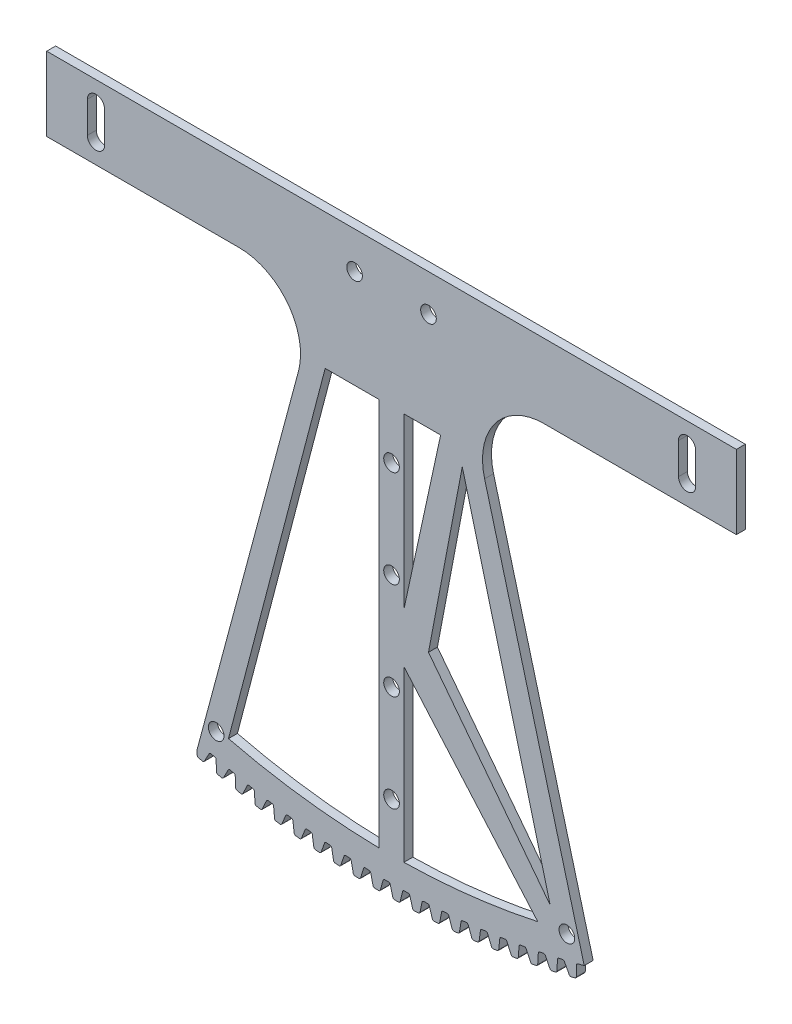
SolidWorks part; units mm, degrees
material "201 Annealed Stainless Steel (SS)"
ref_plane "Front Plane" through (0, 0, 0) normal (0, 0, 1) x (1, 0, 0)
ref_plane "Top Plane" through (0, 0, 0) normal (0, 1, 0) x (1, 0, 0)
ref_plane "Right Plane" through (0, 0, 0) normal (1, 0, 0) x (0, 0, -1)
sketch "Sketch3" plane through (0, 0, 0) normal (0, 0, 1) x (1, 0, 0)
  line L0 (0, 0) -> (0, -304.8) construction
  line L1 (-21.234, -79.2464) -> (-78.888, -294.4142)
  line L2 (21.234, -79.2464) -> (78.888, -294.4142)
  line L4 (-140, -79.56) -> (140, -79.56)
  line L5 (-140, -79.56) -> (-140, -109.56)
  line L6 (-140, -109.56) -> (140, -109.56)
  line L7 (140, -79.56) -> (140, -109.56)
  line L8 (0, -109.56) -> (0, -79.56) construction
  line L9 (-140, -94.56) -> (140, -94.56) construction
  arc A0 (-78.888, -294.4142) -> (78.888, -294.4142) centre (0, 0) ccw
  point P269 (0, -94.56)
  dimension "D1" = 304.8
  dimension "D4" = 79.56
  dimension "D5" = 30
  dimension "D6" = 280
  dimension "D7" = 140
extrude "Boss-Extrude2" add sketch "Sketch3" along normal blind 3.6286 contours L7 L4 L2 L6 | L1 L6 L2 L4 | L1 L4 L2 | L5 L6 L1 L4 | L1 A0 L2 L6
fillet "Fillet1" radius 25 2 edges at (-29.3565, -109.56, 1.8143) (29.3565, -109.56, 1.8143)
sketch "Sketch4" plane through (0, -79.56, 0) normal (0, 1, 0) x (1, 0, 0)
  line L1 (-140, 0) -> (140, 0)
  line L2 (-140, 0) -> (-140, -3.6286)
  line L3 (-140, -3.6286) -> (140, -3.6286)
  line L4 (140, 0) -> (140, -3.6286)
  line L5 (0, -3.6286) -> (0, 0) construction
  line L6 (-140, -1.8143) -> (140, -1.8143) construction
  point P252 (0, -1.8143)
sketch "Sketch5" plane through (0, 0, 0) normal (0, 0, -1) x (-1, 0, 0)
  line L0 (-123.5, -94.56) -> (-123.5, -100.91)
  line L1 (-116.5, -94.56) -> (-116.5, -100.91)
  line L2 (116.5, -94.56) -> (116.5, -88.21)
  line L3 (140, -79.56) -> (-140, -79.56) construction
  line L4 (-120, -88.21) -> (-120, -100.91) construction
  line L5 (0, -79.56) -> (0, -109.56) construction
  line L6 (-116.5, -94.56) -> (-116.5, -88.21)
  line L7 (-123.5, -94.56) -> (-123.5, -88.21)
  line L8 (116.5, -94.56) -> (116.5, -100.91)
  line L9 (123.5, -94.56) -> (123.5, -100.91)
  line L10 (123.5, -94.56) -> (123.5, -88.21)
  line L11 (-140, -79.56) -> (-140, -109.56) construction
  line L12 (120, -88.21) -> (120, -100.91) construction
  arc A1 (-116.5, -88.21) -> (-123.5, -88.21) centre (-120, -88.21) ccw
  arc A2 (-123.5, -100.91) -> (-116.5, -100.91) centre (-120, -100.91) ccw
  arc A3 (123.5, -100.91) -> (116.5, -100.91) centre (120, -100.91) cw
  arc A4 (116.5, -88.21) -> (123.5, -88.21) centre (120, -88.21) cw
  circle A5 centre (-15, -94.56) radius 3.175
  circle A6 centre (15, -94.56) radius 3.175
  dimension "D1" = 16.5
  dimension "D2" = 7
  dimension "D3" = 8.65
  dimension "D5" = 3.5
  dimension "D6" = 15
  dimension "D8" = 6.35
  dimension "D4" = 6.35
  dimension "D7" = 15
sketch "Sketch13" plane through (0, 0, 0) normal (0, 0, -1) x (-1, 0, 0)
  line L0 (0, 0) -> (78.888, -294.4142)
  line L1 (0, 0) -> (-78.888, -294.4142)
  arc A0 (-78.888, -294.4142) -> (78.888, -294.4142) centre (0, 0) ccw
  arc A1 (-78.888, -294.4142) -> (78.888, -294.4142) centre (0, 0) ccw construction
  arc A2 (-78.888, -294.4142) -> (78.888, -294.4142) centre (0, 0) ccw
  circle A3 centre (0, 0) radius 304.8
  dimension "D1" = 609.6
sketch "Sketch14" plane through (0, 0, 0) normal (0, 0, -1) x (-1, 0, 0)
  line L0 (0, 0) -> (80.0203, -298.6399) construction
  line L2 (78.888, -294.4142) -> (78.9109, -297.0369)
  line L3 (78.9109, -297.0369) -> (76.2891, -297.7211)
  line L18 (76.2891, -297.7211) -> (75.0275, -295.4216)
  line L20 (0, 0) -> (-79.2746, -295.8555) construction
  line L32 (78.888, -294.4142) -> (75.0275, -295.4216)
  line L33 (75.0275, -295.4216) -> (78.888, -294.4142)
  line L34 (0, 0) -> (-75.3952, -296.8678) construction
  line L35 (0, 0) -> (-71.5028, -297.8293) construction
  line L36 (0, 0) -> (-67.5982, -298.7397) construction
  line L37 (0, 0) -> (-63.6821, -299.5989) construction
  line L38 (0, 0) -> (-59.755, -300.4068) construction
  line L39 (0, 0) -> (-55.8176, -301.1633) construction
  line L40 (0, 0) -> (-51.8707, -301.8681) construction
  line L41 (0, 0) -> (-47.9149, -302.5212) construction
  line L42 (0, 0) -> (-43.951, -303.1225) construction
  line L43 (0, 0) -> (-39.9794, -303.6718) construction
  line L44 (0, 0) -> (-36.0011, -304.1691) construction
  line L45 (0, 0) -> (-32.0165, -304.6143) construction
  line L46 (0, 0) -> (-28.0265, -305.0073) construction
  line L47 (0, 0) -> (-24.0316, -305.348) construction
  line L48 (0, 0) -> (-20.0327, -305.6364) construction
  line L49 (0, 0) -> (-16.0303, -305.8724) construction
  line L50 (0, 0) -> (-12.0252, -306.0561) construction
  line L51 (0, 0) -> (-8.018, -306.1873) construction
  line L52 (0, 0) -> (-4.0094, -306.266) construction
  line L53 (0, 0) -> (-0.0002, -306.2922) construction
  line L54 (0, 0) -> (4.0091, -306.266) construction
  line L55 (0, 0) -> (8.0176, -306.1873) construction
  line L56 (0, 0) -> (12.0248, -306.0561) construction
  line L57 (0, 0) -> (16.03, -305.8725) construction
  line L58 (0, 0) -> (20.0323, -305.6364) construction
  line L59 (0, 0) -> (24.0313, -305.348) construction
  line L60 (0, 0) -> (28.0261, -305.0073) construction
  line L61 (0, 0) -> (32.0162, -304.6143) construction
  line L62 (0, 0) -> (36.0007, -304.1691) construction
  line L63 (0, 0) -> (39.9791, -303.6719) construction
  line L64 (0, 0) -> (43.9506, -303.1225) construction
  line L65 (0, 0) -> (47.9146, -302.5213) construction
  line L66 (0, 0) -> (51.8704, -301.8682) construction
  line L67 (0, 0) -> (55.8173, -301.1633) construction
  line L68 (0, 0) -> (59.7546, -300.4069) construction
  line L69 (0, 0) -> (63.6817, -299.599) construction
  line L70 (0, 0) -> (67.5979, -298.7398) construction
  line L71 (0, 0) -> (71.5025, -297.8293) construction
  line L72 (0, 0) -> (75.3948, -296.8679) construction
  line L73 (0, 0) -> (-79.2746, -295.8555) construction
  line L74 (0, 0) -> (-75.3952, -296.8678) construction
  line L137 (37.789, -141.0305) -> (78.888, -294.4142) construction
  line L138 (-140, -79.56) -> (-140, -109.56)
  line L139 (-140, -109.56) -> (-61.9371, -109.56)
  line L140 (-37.789, -141.0305) -> (-78.888, -294.4142)
  line L141 (78.888, -294.4142) -> (37.789, -141.0305)
  line L142 (61.9371, -109.56) -> (140, -109.56)
  line L143 (140, -109.56) -> (140, -79.56)
  line L144 (140, -79.56) -> (-140, -79.56)
  line L145 (-140, -79.56) -> (-140, -109.56)
  line L146 (-140, -109.56) -> (-61.9371, -109.56)
  line L147 (-37.789, -141.0305) -> (-78.888, -294.4142)
  line L149 (61.9371, -109.56) -> (140, -109.56)
  line L150 (140, -109.56) -> (140, -79.56)
  line L151 (140, -79.56) -> (-140, -79.56)
  circle A0 centre (0, 0) radius 307.34
  circle A1 centre (0, 0) radius 302.26
  arc A3 (-37.789, -141.0305) -> (-61.9371, -109.56) centre (-61.9371, -134.56) ccw
  arc A5 (61.9371, -109.56) -> (37.789, -141.0305) centre (61.9371, -134.56) ccw
  arc A6 (-37.789, -141.0305) -> (-61.9371, -109.56) centre (-61.9371, -134.56) ccw
  arc A8 (61.9371, -109.56) -> (37.789, -141.0305) centre (61.9371, -134.56) ccw
  arc A11 (-78.888, -294.4142) -> (78.888, -294.4142) centre (0, 0) ccw
  arc A12 (-78.888, -294.4142) -> (78.888, -294.4142) centre (0, 0) ccw
  dimension "D5" = 614.68
  dimension "D6" = 30
  dimension "D7" = 40
  dimension "D4" = 604.52
  dimension "D1" = 14.5
  dimension "D3" = 14.5
  dimension "D8" = 0.75
  dimension "D9" = 306.2922
  dimension "D10" = 0.75
  dimension "D2" = 0
extrude "Boss-Extrude4" add sketch "Sketch14" against normal up to surface (3.6286 mm away) up to face at (0, -146.6727, 3.6286)
sketch "Sketch15" plane through (0, 0, 0) normal (1, 0, 0) x (0, 0, -1)
  line L0 (0, 0) -> (-23.3364, 0) construction
sketch "Sketch16" plane through (0, 0, 0) normal (0, 0, -1) x (-1, 0, 0)
  line L0 (75.0275, -295.4216) -> (73.7653, -293.1208)
  line L1 (73.7653, -293.1208) -> (71.1999, -293.7544)
  line L2 (71.1999, -293.7544) -> (71.1541, -296.3784)
  line L3 (0, 0) -> (71.5025, -297.8293) construction
  line L4 (0, 0) -> (75.3948, -296.8679) construction
  circle A0 centre (0, 0) radius 302.26 construction
  arc A1 (-78.888, -294.4142) -> (78.888, -294.4142) centre (0, 0) ccw construction
  dimension "D1" = 14.5
  dimension "D2" = 14.5
extrude "Cut-Extrude2" cut sketch "Sketch16" against normal through all and the other way through all
fillet "Fillet2" radius 0.73 2 edges at (-76.2891, -297.7211, 1.8143) (-78.9109, -297.0369, 1.8143)
pattern_circular "CirPattern8" count 20 every 1.5 about axis through (0, 0, 0) along (0, 0, 1) of "Cut-Extrude2", "Boss-Extrude4", "Fillet2"
extrude "Cut-Extrude3" cut sketch "Sketch5" against normal through all
sketch "Sketch17" plane through (0, 0, 0) normal (0, 0, -1) x (-1, 0, 0)
  line L0 (0, -79.56) -> (0, -134.56) construction
  line L1 (140, -79.56) -> (-140, -79.56) construction
  line L2 (-61.9371, -109.56) -> (61.9371, -109.56) construction
  line L3 (-36.9371, -134.56) -> (-26.9371, -134.56) construction
  line L4 (-36.9371, -134.56) -> (-26.9371, -134.56) construction
  line L5 (-26.9371, -134.56) -> (-66.1944, -284.3612) construction
  line L6 (-66.1944, -284.3612) -> (-76.1944, -284.3612) construction
  line L7 (0, -292.2593) -> (5, -292.2593) construction
  line L8 (-37.789, -141.0305) -> (-78.888, -294.4142) construction
  line L9 (0, -134.56) -> (-5, -134.56) construction
  line L10 (0, -134.56) -> (5, -134.56) construction
  line L11 (26.9371, -134.56) -> (36.9371, -134.56) construction
  line L12 (-5, -134.56) -> (-5, -292.2593) construction
  line L13 (36.9371, -134.56) -> (26.9371, -134.56) construction
  line L14 (26.9371, -134.56) -> (66.1944, -284.3612) construction
  line L15 (66.1944, -284.3612) -> (76.1944, -284.3612) construction
  line L16 (37.789, -141.0305) -> (78.888, -294.4142) construction
  line L17 (0.6571, -302.2593) -> (-3.5916, -302.2593) construction
  line L18 (-5, -134.56) -> (5, -134.56) construction
  line L19 (-3.5916, -292.2593) -> (-5, -292.2593) construction
  line L20 (5, -134.56) -> (5, -292.2593) construction
  line L21 (-3.5916, -302.2593) -> (-3.5916, -292.2593) construction
  line L22 (0, -193.6972) -> (0, -233.1221) construction
  line L24 (-66.1944, -284.3612) -> (-68.6354, -294.3612) construction
  line L25 (-67.3487, -294.6613) -> (-69.9221, -294.0612) construction
  line L26 (71.1999, -293.7544) -> (66.067, -294.9513) construction
  line L27 (66.1944, -284.3612) -> (68.6335, -294.3529) construction
  line L28 (26.9371, -134.56) -> (66.1944, -284.3612)
  line L29 (26.9371, -134.56) -> (5, -134.56)
  line L30 (5, -134.56) -> (5, -292.2593)
  line L31 (-66.1944, -284.3612) -> (-26.9371, -134.56)
  line L32 (-26.9371, -134.56) -> (-5, -134.56)
  line L33 (-5, -134.56) -> (-5, -292.2593)
  line L35 (66.1944, -284.3612) -> (57.6779, -286.2946)
  line L36 (66.1944, -284.3612) -> (64.4199, -277.5899) construction
  line L41 (26.9371, -134.56) -> (28.7117, -141.3313) construction
  line L42 (26.9371, -134.56) -> (19.9371, -134.56) construction
  line L44 (28.7117, -141.3313) -> (26.9371, -134.56) construction
  line L48 (-59.3729, -285.9321) -> (-5, -223.4096)
  line L50 (-64.4199, -277.5899) -> (-15, -213.4096)
  line L51 (-15, -213.4096) -> (-28.7117, -141.3313)
  line L52 (-5, -203.4096) -> (-19.9371, -134.56)
  circle A0 centre (0, -272.5469) radius 3.175
  arc A1 (61.9371, -109.56) -> (37.789, -141.0305) centre (61.9371, -134.56) ccw construction
  arc A2 (-37.789, -141.0305) -> (-61.9371, -109.56) centre (-61.9371, -134.56) ccw construction
  arc A3 (-66.1944, -284.3612) -> (-5, -292.2593) centre (0, -12.5018) ccw
  arc A4 (5, -292.2593) -> (66.1944, -284.3612) centre (0, -12.5018) ccw
  circle A5 centre (0, -233.1221) radius 3.175
  circle A6 centre (0, -193.6972) radius 3.175
  circle A7 centre (0, -154.2724) radius 3.175
  circle A8 centre (-71.1944, -284.3612) radius 3.175
  circle A9 centre (71.1944, -284.3612) radius 3.175
  arc A13 (19.9371, -134.56) -> (28.7117, -141.3313) centre (26.9371, -134.56) ccw construction
  arc A14 (19.9371, -134.56) -> (28.7117, -141.3313) centre (26.9371, -134.56) ccw construction
  arc A15 (-59.3729, -285.9321) -> (-64.4199, -277.5899) centre (-66.1944, -284.3612) ccw construction
  arc A16 (-64.4199, -277.5899) -> (-59.3729, -285.9321) centre (-66.1944, -284.3612) cw
  arc A17 (-5, -203.4096) -> (-5, -223.4096) centre (-5, -213.4096) ccw construction
  arc A18 (-28.7117, -141.3313) -> (-19.9371, -134.56) centre (-26.9371, -134.56) ccw construction
  arc A19 (5, -223.4096) -> (5, -203.4096) centre (5, -213.4096) ccw construction
  arc A20 (64.4199, -277.5899) -> (59.3729, -285.9321) centre (66.1944, -284.3612) ccw construction
  dimension "D13" = 6.35
  dimension "D14" = 6.35
  dimension "D15" = 10
  dimension "D16" = 7
  dimension "D17" = 7
  dimension "D20" = 7
  dimension "D21" = 10
  dimension "D22" = 7
  dimension "D18" = 7
  dimension "D1" = 10
  dimension "D2" = 5
  dimension "D3" = 10
  dimension "D4" = 10
  dimension "D5" = 5
  dimension "D6" = 5
  dimension "D7" = 10
  dimension "D8" = 10
  dimension "D9" = 5
  dimension "D10" = 10
  dimension "D11" = 157.6993
  dimension "D12" = 10
  dimension "D19" = 12.241
extrude "Cut-Extrude4" cut sketch "Sketch17" against normal through all
fillet "Fillet3" radius 0.7 39 edges at (75.039, -292.7973, 1.8143) (69.9221, -294.0612, 1.8143) (67.3487, -294.6613, 1.8143) (62.2005, -295.7908, 1.8143) (59.6123, -296.3233, 1.8143) (54.4363, -297.3177, 1.8143) (51.835, -297.7822, 1.8143) (46.6348, -298.6408, 1.8143) (44.0223, -299.037, 1.8143) (38.8013, -299.7592, 1.8143) (36.1793, -300.0869, 1.8143) (30.9412, -300.6722, 1.8143) (28.3115, -300.9312, 1.8143) (23.06, -301.3791, 1.8143) (20.4244, -301.5692, 1.8143) (15.1629, -301.8794, 1.8143) (12.5232, -302.0005, 1.8143) (7.2554, -302.1729, 1.8143) (4.6135, -302.2248, 1.8143) (-0.6571, -302.2593, 1.8143) (-3.2994, -302.242, 1.8143) (-8.5691, -302.1385, 1.8143) (-11.2101, -302.0521, 1.8143) (-16.4752, -301.8107, 1.8143) (-19.113, -301.6551, 1.8143) (-24.37, -301.276, 1.8143) (-27.0029, -301.0514, 1.8143) (-32.2482, -300.5348, 1.8143) (-34.8743, -300.2414, 1.8143) (-40.1042, -299.5877, 1.8143) (-42.7217, -299.2256, 1.8143) (-47.9327, -298.4352, 1.8143) (-50.5399, -298.0047, 1.8143) (-55.7284, -297.0782, 1.8143) (-58.3234, -296.5796, 1.8143) (-63.4859, -295.5176, 1.8143) (-66.067, -294.9513, 1.8143) (-71.1999, -293.7544, 1.8143) (-73.7653, -293.1208, 1.8143)
sketch "Sketch18" plane through (0, 0, 3.6286) normal (0, 0, 1) x (1, 0, 0)
  line L0 (37.789, -141.0305) -> (78.8881, -294.4142) construction
  line L1 (78.2307, -291.9607) -> (79.311, -294.4543)
  line L2 (79.311, -294.4543) -> (78.619, -294.5581)
  line L3 (78.619, -294.5581) -> (77.5958, -292.1301)
  arc A0 (77.5958, -292.1301) -> (78.2307, -291.9607) centre (0, 0) ccw
extrude "Cut-Extrude5" cut sketch "Sketch18" against normal through all
equation "\"D7@Sketch3\"=\"D6@Sketch3\"/2"
